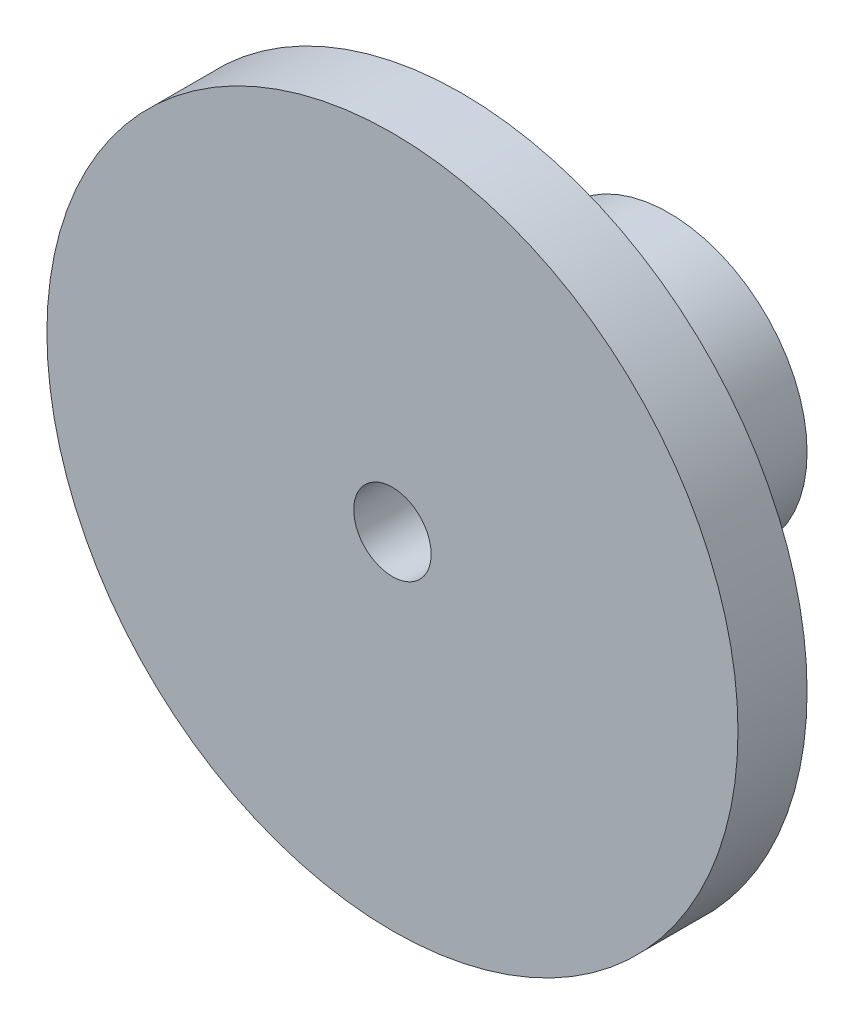
SolidWorks part; units mm, degrees
ref_plane "Plan de face" through (0, 0, 0) normal (0, 0, 1) x (1, 0, 0)
ref_plane "Plan de dessus" through (0, 0, 0) normal (0, 1, 0) x (1, 0, 0)
ref_plane "Plan de droite" through (0, 0, 0) normal (1, 0, 0) x (0, 0, -1)
sketch "Esquisse1" plane through (0, 0, 0) normal (0, 0, 1) x (1, 0, 0)
  circle A0 centre (0, 0) radius 25
  circle A1 centre (0, 0) radius 2.8
  point P12 (-18.2018, 0)
  dimension "D1" = 50
  dimension "D2" = 5.6
extrude "Boss.-Extru.1" add sketch "Esquisse1" along normal blind 5
sketch "Esquisse2" plane through (0, 0, 0) normal (0, 0, -1) x (-1, 0, 0)
  circle A0 centre (0, 0) radius 10
  circle A1 centre (0, 0) radius 2.8
  dimension "D1" = 20
  dimension "D2" = 5.6
extrude "Boss.-Extru.2" add sketch "Esquisse2" along normal blind 15
